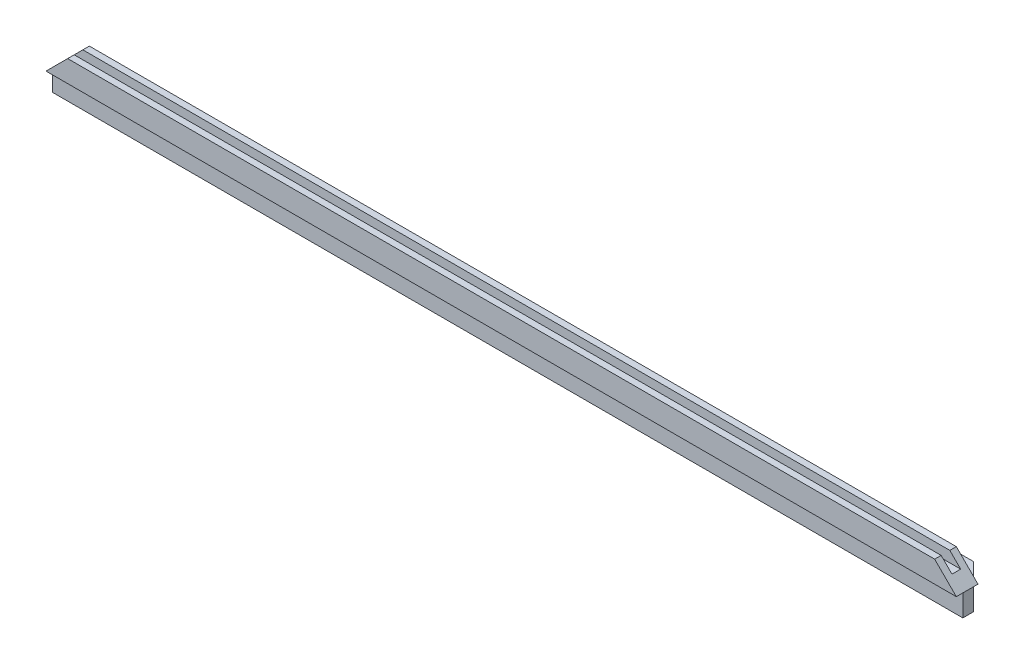
SolidWorks part; units mm, degrees
ref_plane "前视基准面" through (0, 0, 0) normal (0, 0, 1) x (1, 0, 0)
ref_plane "上视基准面" through (0, 0, 0) normal (0, 1, 0) x (1, 0, 0)
ref_plane "右视基准面" through (0, 0, 0) normal (1, 0, 0) x (0, 0, -1)
other "Configuration Table"
sketch "草图2" plane through (0, 0, 0) normal (0, 1, 0) x (1, 0, 0)
  line L0 (-130.6414, -36.9259) -> (289.3586, -36.9259)
  line L1 (-125.6414, -31.9259) -> (284.3586, -31.9259)
  line L2 (-130.6414, -36.9259) -> (-125.6414, -31.9259)
  line L3 (284.3586, -31.9259) -> (289.3586, -36.9259)
  dimension "D1" = 420
  dimension "D2" = 410
  dimension "D3" = 5
  dimension "D4" = 45
  dimension "D5" = 45
extrude "凸台-拉伸2" add sketch "草图2" along normal blind 4
ref_plane "基准面2" through (0, 2, 0) normal (0, 1, 0) x (1, 0, 0)
sketch "草图3" plane through (0, 4, 0) normal (0, 1, 0) x (1, 0, 0)
  line L0 (-130.6414, -36.9259) -> (-120.6414, -26.9259)
  line L1 (-130.6414, -36.9259) -> (289.3586, -36.9259)
  line L3 (-120.6414, -26.9259) -> (279.3586, -26.9259)
  line L5 (289.3586, -36.9259) -> (279.3586, -26.9259)
  dimension "D1" = 45
  dimension "D2" = 420
  dimension "D3" = 45
  dimension "D4" = 10
extrude "凸台-拉伸3" add sketch "草图3" along normal blind 3
mirror "镜向1" about plane through (0, 2, 0) normal (0, 1, 0) of "凸台-拉伸3"
sketch "草图5" plane through (0, 0, 36.9259) normal (0, 0, 1) x (1, 0, 0)
  line L1 (-130.6414, 7) -> (289.3586, 7)
  line L2 (-130.6414, 7) -> (-130.6414, -3)
  line L3 (-130.6414, -3) -> (289.3586, -3)
  line L4 (289.3586, 7) -> (289.3586, -3)
  dimension "D1" = 10
  dimension "D2" = 420
extrude "凸台-拉伸4" add sketch "草图5" along normal blind 5
ref_plane "基准面3" through (0, 0, 41.9259) normal (0, 0, 1) x (1, 0, 0)
sketch "草图7" plane through (0, 0, 41.9259) normal (0, 0, 1) x (1, 0, 0)
  line L1 (-130.6414, 7) -> (289.3586, 7)
  line L2 (-125.6414, 12) -> (284.3586, 12)
  line L3 (-125.6414, 12) -> (-130.6414, 7)
  line L4 (284.3586, 12) -> (289.3586, 7)
  dimension "D1" = 5
  dimension "D2" = 45
  dimension "D3" = 45
extrude "凸台-拉伸5" add sketch "草图7" against normal blind 4
ref_plane "基准面4" through (0, 0, 39.9259) normal (0, 0, -1) x (-1, 0, 0)
sketch "草图8" plane through (0, 0, 37.9259) normal (0, 0, -1) x (-1, 0, 0)
  line L0 (-289.3586, 7) -> (-279.3586, 17)
  line L1 (-289.3586, 7) -> (130.6414, 7)
  line L3 (-279.3586, 17) -> (120.6414, 17)
  line L5 (130.6414, 7) -> (120.6414, 17)
  dimension "D1" = 45
  dimension "D2" = 420
  dimension "D3" = 45
  dimension "D4" = 10
extrude "凸台-拉伸6" add sketch "草图8" along normal blind 3
mirror "镜向2" about plane through (0, 0, 39.9259) normal (0, 0, -1) of "凸台-拉伸6"
